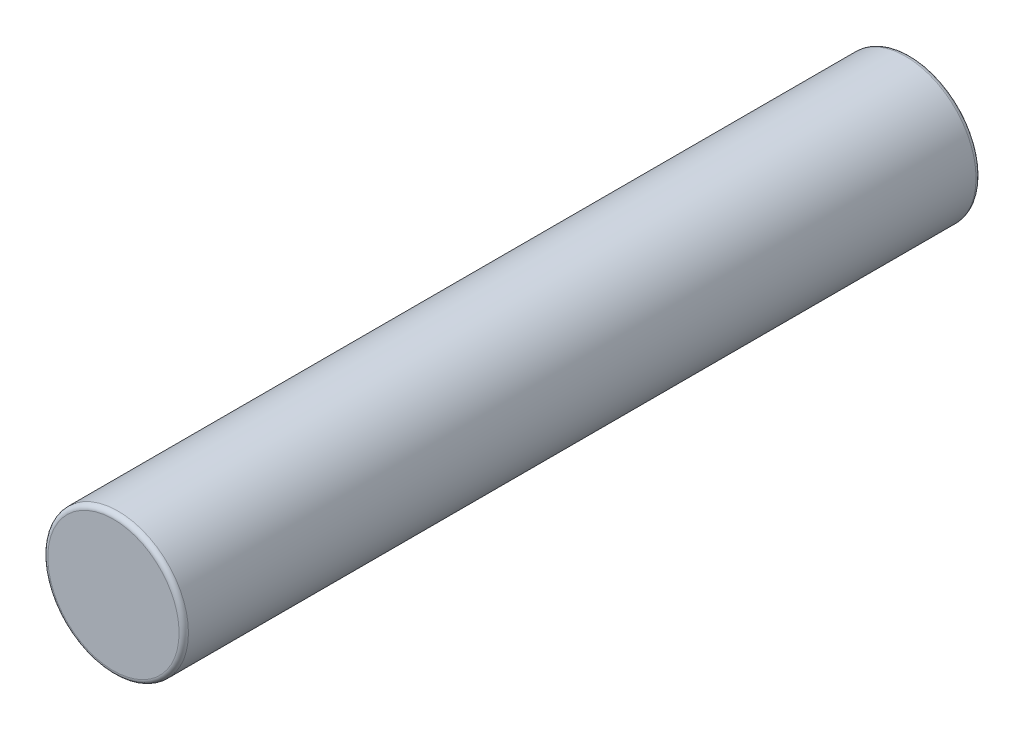
SolidWorks part; units mm, degrees
ref_plane "Front Plane" through (0, 0, 0) normal (0, 0, 1) x (1, 0, 0)
ref_plane "Top Plane" through (0, 0, 0) normal (0, 1, 0) x (1, 0, 0)
ref_plane "Right Plane" through (0, 0, 0) normal (1, 0, 0) x (0, 0, -1)
sketch "Sketch1" plane through (0, 0, 0) normal (0, 0, 1) x (1, 0, 0)
  circle A0 centre (0, 0) radius 3
  dimension "D1" = 6
extrude "Boss-Extrude1" add sketch "Sketch1" along normal blind 34 contours A0
fillet "Fillet1" radius 0.2 2 edges at (3, 0, 0) (3, 0, 34)
